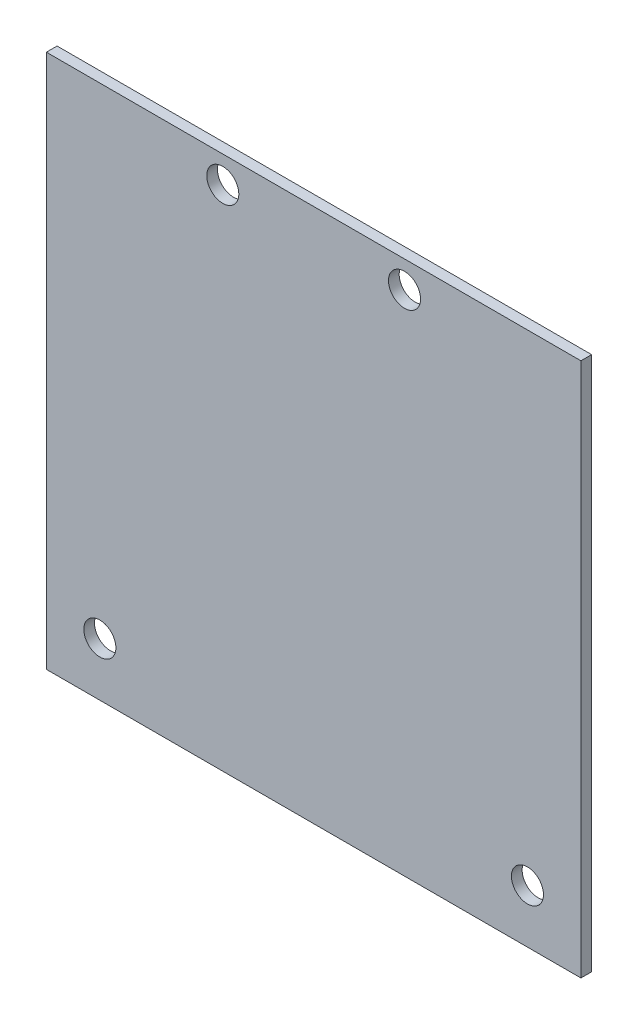
SolidWorks part; units mm, degrees
ref_plane "Ön Düzlem" through (0, 0, 0) normal (0, 0, 1) x (1, 0, 0)
ref_plane "Üst Düzlem" through (0, 0, 0) normal (0, 1, 0) x (1, 0, 0)
ref_plane "Sağ Düzlem" through (0, 0, 0) normal (1, 0, 0) x (0, 0, -1)
sketch "Çizim1" plane through (0, 0, 0) normal (0, 0, 1) x (1, 0, 0)
  line L0 (16.5, 47.5) -> (33.5, 47.5) construction
  line L1 (0, 0) -> (50, 0)
  line L2 (0, 0) -> (0, 50)
  line L3 (0, 50) -> (50, 50)
  line L4 (50, 0) -> (50, 50)
  circle A0 centre (16.5, 47.5) radius 1.5
  circle A1 centre (33.5, 47.5) radius 1.5
  circle A2 centre (5, 5) radius 1.5
  circle A3 centre (45, 5) radius 1.5
  dimension "D3" = 3
  dimension "D4" = 16.5
  dimension "D7" = 3
  dimension "D8" = 5
  dimension "D9" = 5
  dimension "D10" = 5
  dimension "D11" = 5
  dimension "D1" = 50
  dimension "D2" = 50
  dimension "D5" = 33.5
  dimension "D6" = 2.5
extrude "Yükseklik-Ekstrüzyon1" add sketch "Çizim1" along normal blind 1
